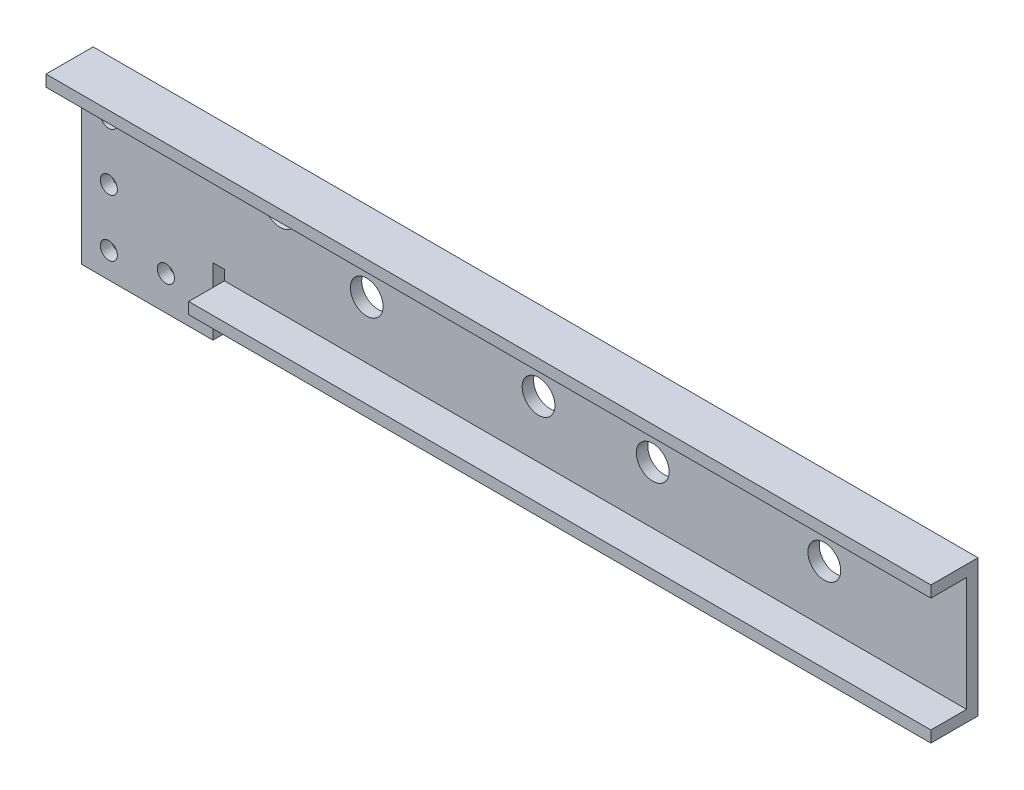
SolidWorks part; units mm, degrees
ref_plane "Front Plane" through (0, 0, 0) normal (0, 0, 1) x (1, 0, 0)
ref_plane "Top Plane" through (0, 0, 0) normal (0, 1, 0) x (1, 0, 0)
ref_plane "Right Plane" through (0, 0, 0) normal (1, 0, 0) x (0, 0, -1)
sketch "Sketch1" plane through (0, 0, 0) normal (0, 0, 1) x (1, 0, 0)
  line L1 (0, 0) -> (155, 0)
  line L2 (0, 0) -> (0, -32)
  line L3 (0, -32) -> (155, -32)
  line L4 (155, 0) -> (155, -32)
  dimension "D1" = 32
  dimension "D2" = 155
extrude "Boss-Extrude1" add sketch "Sketch1" along normal blind 2
sketch "Sketch2" plane through (0, 0, 2) normal (0, 0, 1) x (1, 0, 0)
  line L0 (0, 0) -> (0, -32) construction
  line L1 (155, 0) -> (0, 0)
  line L2 (155, 0) -> (155, -2)
  line L3 (155, -2) -> (0, -2)
  line L4 (0, 0) -> (0, -2)
  line L6 (155, -24) -> (25, -24)
  line L7 (155, -24) -> (155, -22)
  line L8 (155, -22) -> (25, -22)
  line L9 (25, -24) -> (25, -22)
  dimension "D1" = 2
  dimension "D2" = 130
  dimension "D3" = 20
extrude "Boss-Extrude2" add sketch "Sketch2" along normal blind 6.25
sketch "Sketch3" plane through (0, 0, 2) normal (0, 0, 1) x (1, 0, 0)
  line L0 (25, -22) -> (25, -24) construction
  line L1 (155, -32) -> (23, -32)
  line L2 (155, -32) -> (155, -24)
  line L3 (155, -24) -> (25, -24)
  line L4 (23, -32) -> (23, -24)
  line L5 (23, -24) -> (23, -20.25)
  line L6 (0, -32) -> (155, -32) construction
  line L7 (23, -20.25) -> (25, -20.25)
  line L8 (25, -24) -> (25, -20.25)
  point P7 (25, -23)
  dimension "D1" = 2
  dimension "D2" = 11.75
extrude "Cut-Extrude1" cut sketch "Sketch3" against normal blind 6.25
sketch "Sketch4" plane through (0, 0, 2) normal (0, 0, 1) x (1, 0, 0)
  line L0 (4.75, -16) -> (4.75, -29) construction
  line L1 (4.75, -19) -> (4.75, -6) construction
  line L2 (0, -32) -> (23, -32) construction
  line L3 (6.25, -27.5) -> (0, -27.5) construction
  line L4 (0, -2) -> (0, -32) construction
  circle A0 centre (4.75, -27.5) radius 1.5
  circle A1 centre (4.75, -17.5) radius 1.5
  circle A2 centre (4.75, -7.5) radius 1.5
  dimension "D1" = 13
  dimension "D2" = 13
  dimension "D3" = 3
  dimension "D4" = 6.25
extrude "Cut-Extrude2" cut sketch "Sketch4" against normal blind 6.25
sketch "Sketch5" plane through (0, 0, 2) normal (0, 0, 1) x (1, 0, 0)
  line L0 (155, -12) -> (0, -12) construction
  line L1 (155, -22) -> (155, -2) construction
  line L2 (0, -2) -> (0, -32) construction
  line L3 (127.2, -12) -> (155, -12) construction
  line L4 (97.15, -12) -> (132.95, -12) construction
  line L5 (77.15, -12) -> (102.9, -12) construction
  line L6 (47.05, -12) -> (82.9, -12) construction
  circle A0 centre (130.075, -12) radius 2.875
  circle A1 centre (100.025, -12) radius 2.875
  circle A2 centre (80.025, -12) radius 2.875
  circle A3 centre (49.925, -12) radius 2.875
  dimension "D1" = 5.75
  dimension "D3" = 35.8
  dimension "D2" = 27.8
  dimension "D4" = 25.75
  dimension "D5" = 35.85
extrude "Cut-Extrude3" cut sketch "Sketch5" against normal blind 6.25
ref_plane "Plane1" through (4.75, 0, 0) normal (-1, 0, 0) x (0, 0, 1)
sketch "Sketch6" plane through (0, 0, 2) normal (0, 0, 1) x (1, 0, 0)
  circle A3 centre (14.75, -26) radius 1.5
  circle A4 centre (14.75, -6) radius 1.5
  circle A5 centre (34.75, -6) radius 1.5
extrude "Cut-Extrude4" cut sketch "Sketch6" against normal blind 6
chamfer "Chamfer1" distance 1.5 angle 45 1 edges at (36.25, -6, 2)
